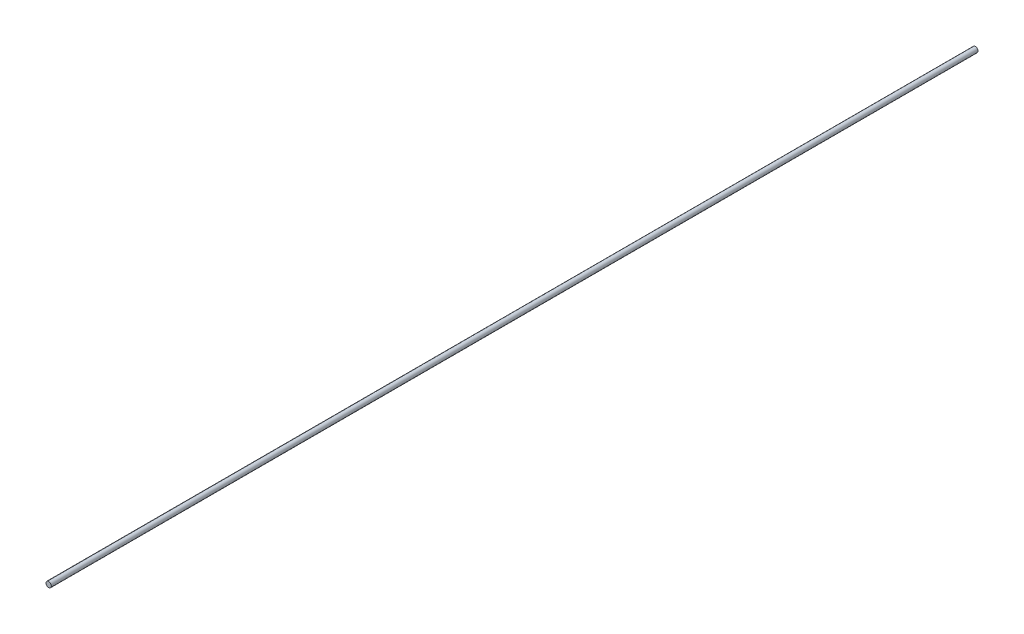
SolidWorks part; units mm, degrees
ref_plane "Front Plane" through (0, 0, 0) normal (1, 0, 0) x (0, 1, 0)
ref_plane "Top Plane" through (0, 0, 0) normal (0, 0, 1) x (0, 1, 0)
ref_plane "Right Plane" through (0, 0, 0) normal (0, 1, 0) x (-1, 0, 0)
sketch "Sketch1" plane through (0, 0, 0) normal (0, 0, 1) x (0, 1, 0)
  circle A0 centre (0, 0) radius 3.175
  dimension "D1" = 6.35
extrude "Boss-Extrude1" add sketch "Sketch1" along normal blind 1104.9
